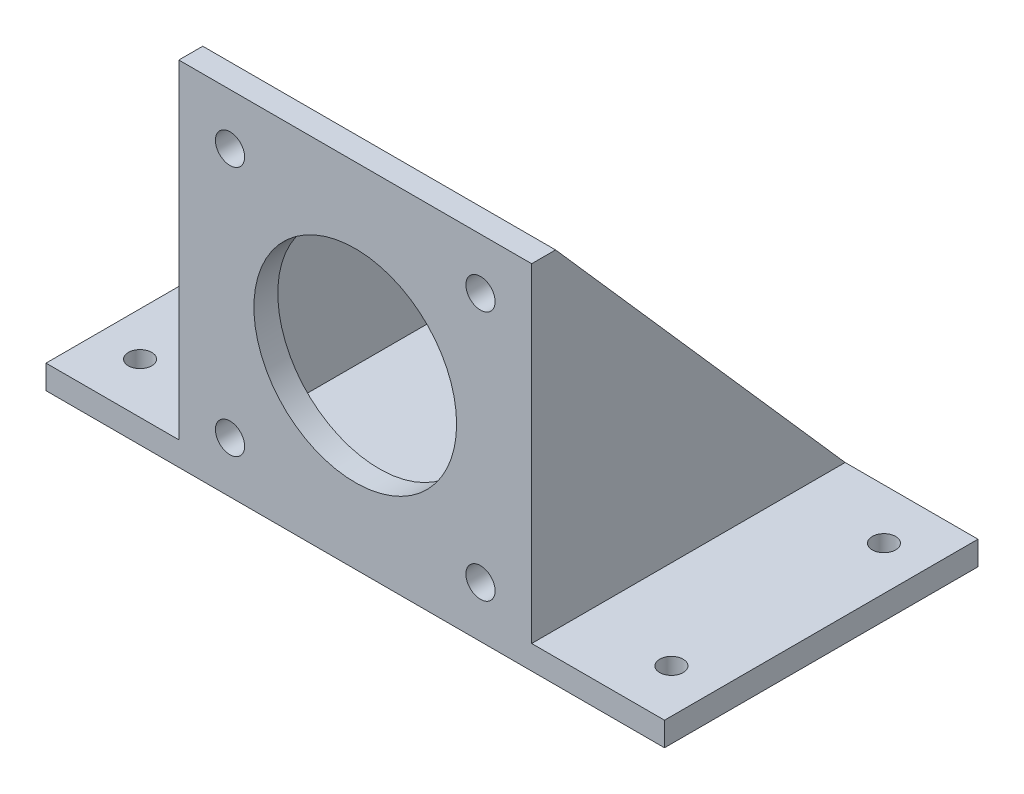
SolidWorks part; units mm, degrees
ref_plane "Front Plane" through (0, 0, 0) normal (0, 0, 1) x (1, 0, 0)
ref_plane "Top Plane" through (0, 0, 0) normal (0, 1, 0) x (1, 0, 0)
ref_plane "Right Plane" through (0, 0, 0) normal (1, 0, 0) x (0, 0, -1)
sketch "Sketch1" plane through (0, 0, 0) normal (0, 0, 1) x (1, 0, 0)
  line L1 (0, 0) -> (66.4, 0)
  line L2 (0, 0) -> (0, 66.4)
  line L3 (0, 66.4) -> (66.4, 66.4)
  line L4 (66.4, 0) -> (66.4, 66.4)
  dimension "D1" = 66.4
  dimension "D2" = 66.4
extrude "Boss-Extrude1" add sketch "Sketch1" along normal blind 59
sketch "Sketch2" plane through (0, 0, 59) normal (0, 0, 1) x (1, 0, 0)
  line L0 (0, 66.4) -> (66.4, 0) construction
  line L2 (9.63, 9.63) -> (56.77, 9.63) construction
  line L3 (9.63, 9.63) -> (9.63, 56.77) construction
  line L4 (9.63, 56.77) -> (56.77, 56.77) construction
  line L5 (56.77, 9.63) -> (56.77, 56.77) construction
  line L6 (9.63, 9.63) -> (56.77, 56.77) construction
  line L7 (9.63, 56.77) -> (56.77, 9.63) construction
  circle A0 centre (33.2, 33.2) radius 19.075
  circle A1 centre (9.63, 56.77) radius 2.75
  circle A2 centre (56.77, 56.77) radius 2.75
  circle A3 centre (56.77, 9.63) radius 2.75
  circle A4 centre (9.63, 9.63) radius 2.75
  point P4 (33.2, 33.2)
  dimension "D3" = 38.15
  dimension "D4" = 5.5
  dimension "D5" = 5.5
  dimension "D6" = 5.5
  dimension "D7" = 5.5
  dimension "D1" = 47.14
  dimension "D2" = 47.14
extrude "Cut-Extrude1" cut sketch "Sketch2" against normal through all
sketch "Sketch3" plane through (0, 66.4, 0) normal (0, 1, 0) x (1, 0, 0)
  line L0 (0, -59) -> (0, 0) construction
  line L1 (66.4, -59) -> (66.4, 0) construction
  line L2 (66.4, -59) -> (0, -59) construction
  line L3 (0, -59) -> (0, 0) construction
  line L4 (66.4, -59) -> (66.4, 0) construction
  line L5 (66.4, -59) -> (0, -59) construction
  line L6 (61.9, -54.5) -> (61.9, 0)
  line L7 (61.9, -54.5) -> (4.5, -54.5)
  line L8 (4.5, -54.5) -> (4.5, 0)
  line L9 (4.5, 0) -> (61.9, 0)
  dimension "D1" = 4.5
extrude "Cut-Extrude2" cut sketch "Sketch3" against normal blind 61.9
sketch "Sketch4" plane through (66.4, 0, 0) normal (1, 0, 0) x (0, 0, -1)
  line L0 (-54.5, 66.4) -> (0, 66.4) construction
  line L1 (-54.5, 66.4) -> (0, 66.4)
  line L2 (0, 4.5) -> (0, 66.4) construction
  line L3 (0, 4.5) -> (0, 66.4)
  line L4 (-54.5, 66.4) -> (0, 4.5)
extrude "Cut-Extrude3" cut sketch "Sketch4" against normal through all
sketch "Sketch5" plane through (0, 0, 0) normal (0, -1, 0) x (1, 0, 0)
  line L0 (0, 59) -> (66.4, 59) construction
  line L1 (91.4, 59) -> (-25, 59)
  line L2 (91.4, 59) -> (91.4, 0)
  line L3 (91.4, 0) -> (-25, 0)
  line L4 (-25, 59) -> (-25, 0)
  line L5 (0, 0) -> (66.4, 0) construction
  line L6 (0, 59) -> (0, 0) construction
  line L7 (66.4, 59) -> (66.4, 0) construction
  dimension "D1" = 25
  dimension "D2" = 25
extrude "Boss-Extrude2" add sketch "Sketch5" against normal blind 4.5
sketch "Sketch6" plane through (0, 4.5, 0) normal (0, 1, 0) x (1, 0, 0)
  line L0 (-25, 0) -> (91.4, -59) construction
  line L2 (-16.8, -49.5) -> (83.2, -49.5) construction
  line L3 (-16.8, -49.5) -> (-16.8, -9.5) construction
  line L4 (-16.8, -9.5) -> (83.2, -9.5) construction
  line L5 (83.2, -49.5) -> (83.2, -9.5) construction
  line L6 (-16.8, -49.5) -> (83.2, -9.5) construction
  line L7 (-16.8, -9.5) -> (83.2, -49.5) construction
  circle A0 centre (-16.8, -9.5) radius 2.2
  circle A1 centre (-16.8, -49.5) radius 2.2
  circle A2 centre (83.2, -49.5) radius 2.2
  circle A3 centre (83.2, -9.5) radius 2.2
  point P4 (33.2, -29.5)
  dimension "D3" = 4.4
  dimension "D4" = 4.4
  dimension "D5" = 4.4
  dimension "D6" = 4.4
  dimension "D1" = 100
  dimension "D2" = 40
extrude "Cut-Extrude4" cut sketch "Sketch6" against normal through all
